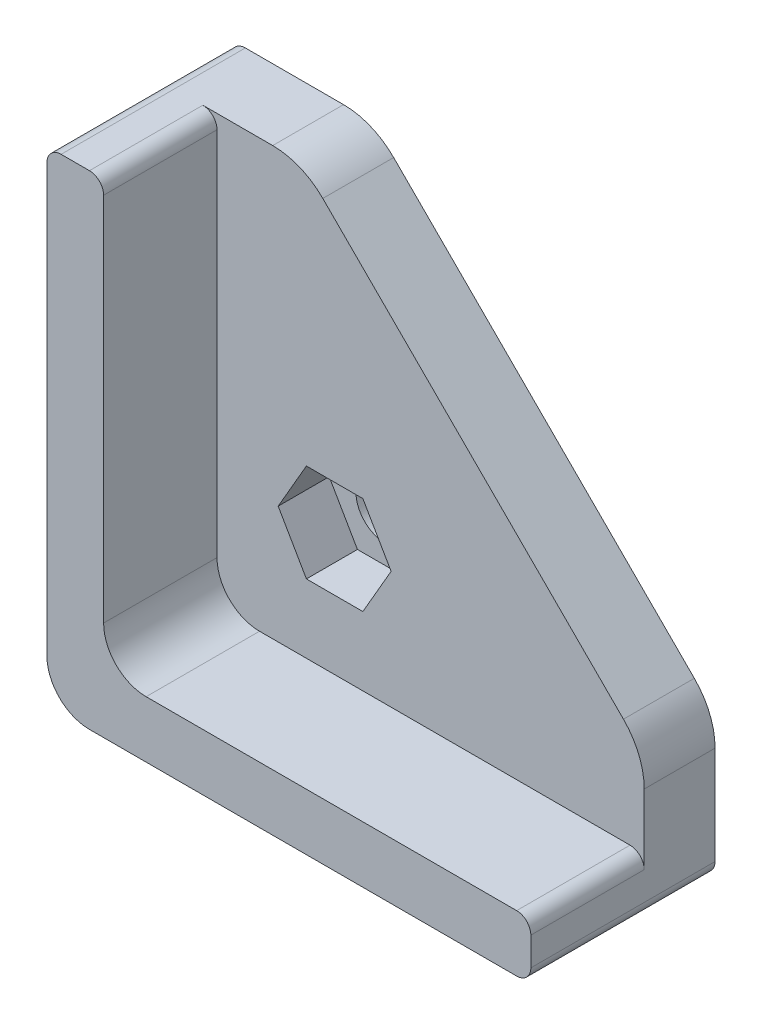
SolidWorks part; units mm, degrees
ref_plane "Front Plane" through (0, 0, 0) normal (0, 0, 1) x (1, 0, 0)
ref_plane "Top Plane" through (0, 0, 0) normal (0, 1, 0) x (1, 0, 0)
ref_plane "Right Plane" through (0, 0, 0) normal (1, 0, 0) x (0, 0, -1)
sketch "Sketch1" plane through (0, 0, 0) normal (0, 0, 1) x (1, 0, 0)
  line L0 (257.4281, -9.6772) -> (223.2859, -9.6772)
  line L1 (210.5859, -9.6772) -> (477.8859, -9.6772) construction
  line L2 (223.2859, -9.6772) -> (223.2859, 24.4649)
  line L3 (223.2859, 257.6228) -> (223.2859, -9.6772) construction
  line L4 (223.2859, 24.4649) -> (233.2859, 24.4649)
  line L5 (233.2859, 24.4649) -> (257.4281, 0.3228)
  line L6 (257.4281, 0.3228) -> (257.4281, -9.6772)
  circle A0 centre (235.5859, 2.6228) radius 2.1 construction
  circle A1 centre (235.5859, 2.6228) radius 2.1
  dimension "D1" = 10
extrude "Boss-Extrude1" add sketch "Sketch1" along normal blind 5
sketch "Sketch2" plane through (0, 0, 5) normal (0, 0, 1) x (1, 0, 0)
  line L0 (257.4281, -9.6772) -> (223.2859, -9.6772)
  line L1 (223.2859, -9.6772) -> (223.2859, 24.4649)
  line L2 (223.2859, 24.4649) -> (227.2859, 24.4649)
  line L3 (233.2859, 24.4649) -> (223.2859, 24.4649) construction
  line L4 (227.2859, 24.4649) -> (227.2859, -5.6772)
  line L5 (227.2859, -5.6772) -> (257.4281, -5.6772)
  line L6 (257.4281, -9.6772) -> (257.4281, 0.3228) construction
  line L7 (257.4281, -5.6772) -> (257.4281, -9.6772)
  dimension "D1" = 4
extrude "Boss-Extrude2" add sketch "Sketch2" along normal blind 8
fillet "Fillet1" radius 3 2 edges at (223.2859, -9.6772, 6.5) (227.2859, -5.6772, 9)
sketch "Sketch3" plane through (0, 0, 5) normal (0, 0, 1) x (1, 0, 0)
  line L1 (239.5696, 2.6228) -> (237.5778, 6.0728)
  line L2 (237.5778, 6.0728) -> (233.5941, 6.0728)
  line L3 (233.5941, 6.0728) -> (231.6022, 2.6228)
  line L4 (231.6022, 2.6228) -> (233.5941, -0.8272)
  line L5 (233.5941, -0.8272) -> (237.5778, -0.8272)
  line L6 (237.5778, -0.8272) -> (239.5696, 2.6228)
  circle A0 centre (235.5859, 2.6228) radius 3.45 construction
  dimension "D1" = 6.9
extrude "Cut-Extrude1" cut sketch "Sketch3" against normal blind 3.6
fillet "Fillet2" radius 5 2 edges at (257.4281, 0.3228, 2.5) (233.2859, 24.4649, 2.5)
fillet "Fillet3" radius 1 4 edges at (257.4281, -5.6772, 9) (257.4281, -9.6772, 6.5) (223.2859, 24.4649, 6.5) (227.2859, 24.4649, 9)
